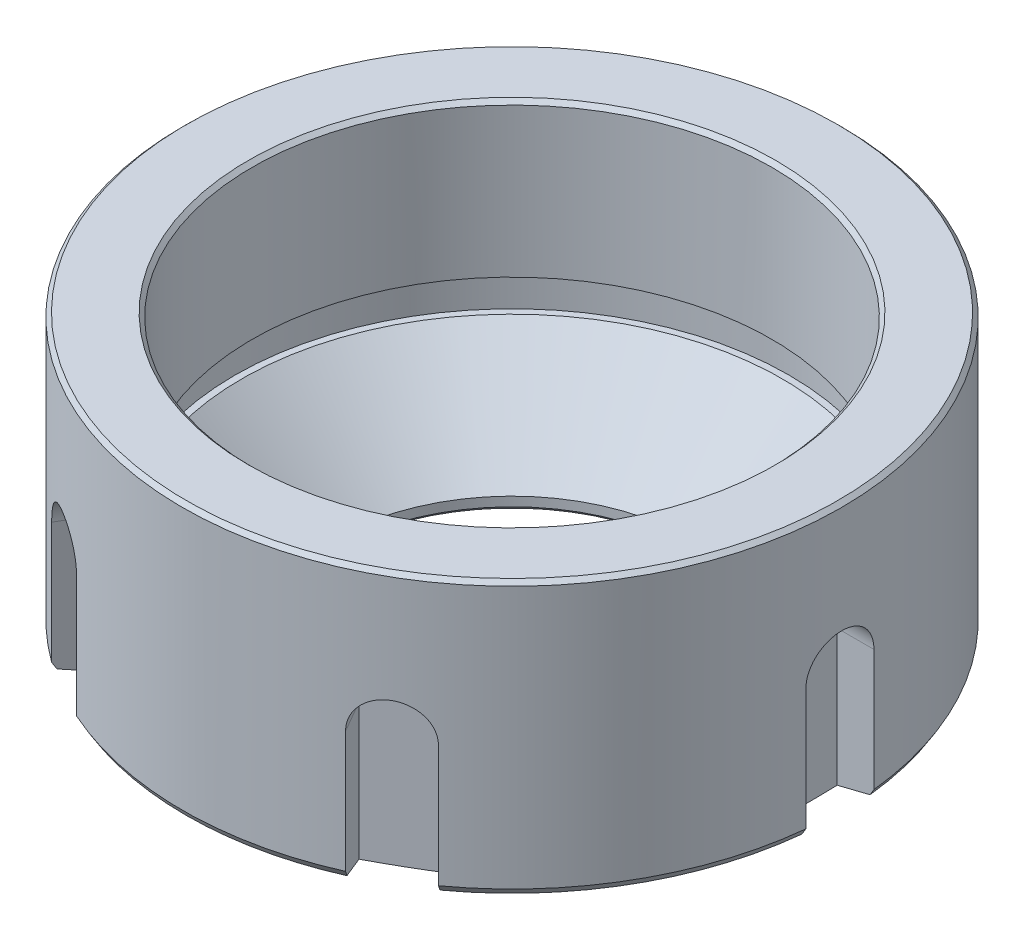
SolidWorks part; units mm, degrees
material "Plain Carbon Steel"
ref_plane "Front Plane" through (0, 0, 0) normal (0, 0, 1) x (1, 0, 0)
ref_plane "Top Plane" through (0, 0, 0) normal (0, 1, 0) x (1, 0, 0)
ref_plane "Right Plane" through (0, 0, 0) normal (1, 0, 0) x (0, 0, -1)
sketch "Sketch1" plane through (0, 0, 0) normal (0, 0, 1) x (1, 0, 0)
  line L0 (0, 0) -> (0, -21.2542) construction
  line L2 (19.7, -15) -> (19.7, -26.6)
  line L3 (19.7, -26.6) -> (21, -26.6)
  line L4 (13.5, -36.6) -> (13.5, -37.6)
  line L5 (13.5, -37.6) -> (25, -37.6)
  line L6 (25, -37.6) -> (25, -15)
  line L7 (25, -15) -> (19.7, -15)
  line L8 (20.5, -29.6) -> (21, -29.6)
  line L9 (21, -29.6) -> (21, -26.6)
  line L10 (13.5, -36.6) -> (20.5, -29.6)
  point P7 (13.5, -29.6)
other "AlignGroup1" parameters "D1"=18.8348, "D2"=18.8348, "D3"=19.5673, "D4"=14, "D5"=18.513, "D6"=0.6, "D8"=3, "D9"=0.5, "D10"=5.3
revolve "Revolve1" add sketch "Sketch1" angle 360 about L0
chamfer "Chamfer1" distance 8 distance2 2 1 edges at (0, -37.6, 25)
chamfer "Chamfer2" distance 0.3 angle 45 4 edges at (0, -35.6, 25) (0, -37.6, 13.5) (0, -15, 25) (0, -15, 19.7)
ref_plane "Plane1" through (-25, 0, 0) normal (-1, 0, 0) x (0, 0, 1)
sketch "Sketch4" plane through (-25, 0, 0) normal (-1, 0, 0) x (0, 0, 1)
  line L0 (0, -37.6) -> (0, -25.98) construction
  line L1 (-17, -37.6) -> (17, -37.6) construction
  line L2 (-2.58, -37.6) -> (-2.58, -25.98)
  line L3 (2.58, -37.6) -> (2.58, -25.98)
  line L7 (20, -15) -> (-20, -15) construction
  arc A0 (-2.58, -37.6) -> (2.58, -37.6) centre (0, -37.6) ccw
  arc A1 (2.58, -25.98) -> (-2.58, -25.98) centre (0, -25.98) ccw
  point P5 (0, -31.79)
  dimension "D2" = 8.4
  dimension "D1" = 5.16
extrude "Cut-Extrude1" cut sketch "Sketch4" against normal blind 2.92
pattern_circular "CirPattern1" count 6 over 360 about axis through (0, 0, 0) along (0, 1, 0) of "Cut-Extrude1"
